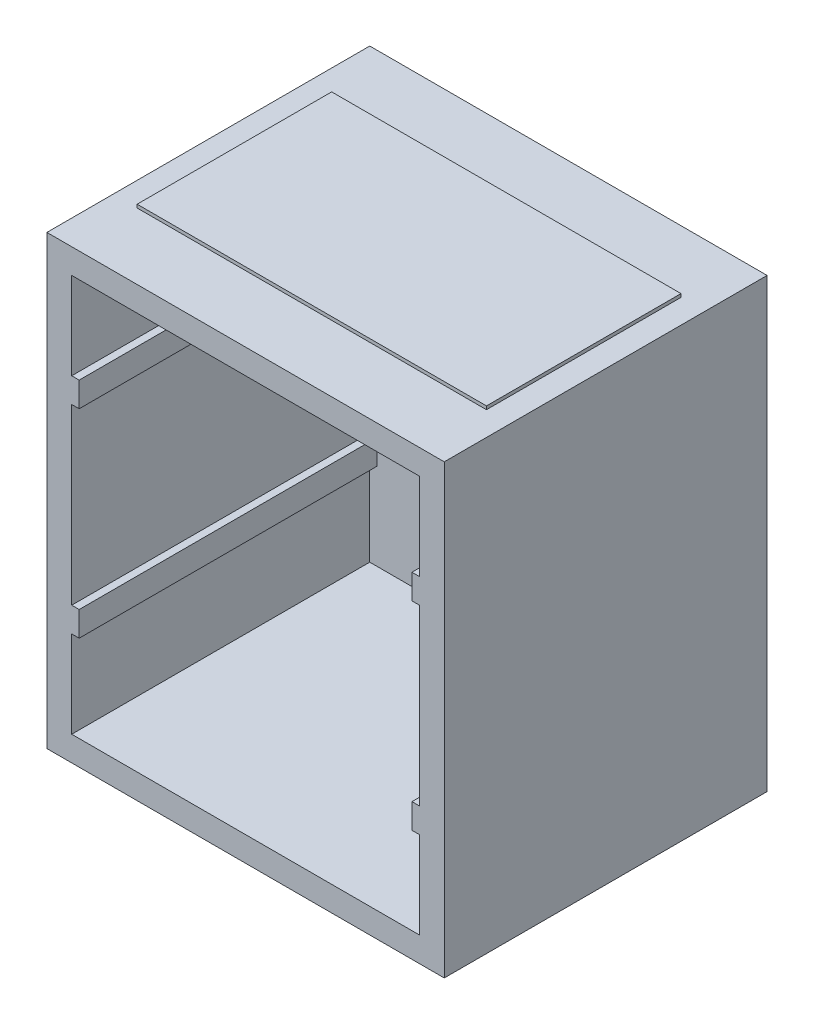
SolidWorks part; units mm, degrees
ref_plane "Front Plane" through (0, 0, 0) normal (0, 0, 1) x (1, 0, 0)
ref_plane "Top Plane" through (0, 0, 0) normal (0, 1, 0) x (1, 0, 0)
ref_plane "Right Plane" through (0, 0, 0) normal (1, 0, 0) x (0, 0, -1)
sketch "Sketch1" plane through (0, 0, 0) normal (0, 0, 1) x (1, 0, 0)
  line L1 (-203.2, 228.6) -> (203.2, 228.6)
  line L2 (-203.2, 228.6) -> (-203.2, -228.6)
  line L3 (-203.2, -228.6) -> (203.2, -228.6)
  line L4 (203.2, 228.6) -> (203.2, -228.6)
  line L5 (-203.2, 228.6) -> (203.2, -228.6) construction
  line L6 (-203.2, -228.6) -> (203.2, 228.6) construction
  point P0 (0, 0)
  dimension "D1" = 457.2
  dimension "D2" = 406.4
extrude "Boss-Extrude1" add sketch "Sketch1" against normal blind 330.2
shell "Shell1" thickness 25.4
sketch "Sketch2" plane through (-177.8, 0, 0) normal (1, 0, 0) x (0, 0, -1)
  line L0 (0, 203.2) -> (0, -203.2) construction
  line L1 (0, -88.9) -> (304.8, -88.9)
  line L2 (0, -88.9) -> (0, -114.3)
  line L3 (0, -114.3) -> (304.8, -114.3)
  line L4 (304.8, -88.9) -> (304.8, -114.3)
  line L5 (304.8, 203.2) -> (304.8, -203.2) construction
  line L6 (304.8, -203.2) -> (0, -203.2) construction
  line L7 (0, 114.3) -> (304.8, 114.3)
  line L8 (0, 88.9) -> (304.8, 88.9)
  line L9 (0, 114.3) -> (0, 88.9)
  line L10 (304.8, 114.3) -> (304.8, 88.9)
  line L11 (304.8, 203.2) -> (0, 203.2) construction
  dimension "D1" = 25.4
  dimension "D2" = 88.9
  dimension "D4" = 88.9
  dimension "D3" = 2
extrude "Boss-Extrude2" add sketch "Sketch2" along normal blind 7.62
mirror "Mirror1" about plane through (0, 0, 0) normal (1, 0, 0) of "Boss-Extrude2"
scale "Scale1" scale about centroid uniform scaling yes scale factor 0.75
sketch "Sketch3" plane through (0, 171.45, 0) normal (0, 1, 0) x (1, 0, 0)
  line L0 (-133.985, 407.9804) -> (-133.985, 249.2304) construction
  line L1 (133.985, 249.2304) -> (-133.985, 249.2304)
  line L2 (133.985, 249.2304) -> (133.985, 100.0054)
  line L3 (133.985, 100.0054) -> (-133.985, 100.0054)
  line L4 (-133.985, 249.2304) -> (-133.985, 100.0054)
  line L5 (133.985, 249.2304) -> (-133.985, 100.0054) construction
  line L6 (133.985, 100.0054) -> (-133.985, 249.2304) construction
  line L7 (133.985, 249.2304) -> (133.985, 407.9804) construction
  line L8 (-133.985, 249.2304) -> (-123.6187, 249.2304) construction
  line L9 (152.4, 49.2054) -> (-152.4, 49.2054) construction
  point P0 (0, 174.6179)
  dimension "D1" = 50.8
extrude "Boss-Extrude3" add sketch "Sketch3" along normal blind 2.54 contours L4 L3 L2 L1
